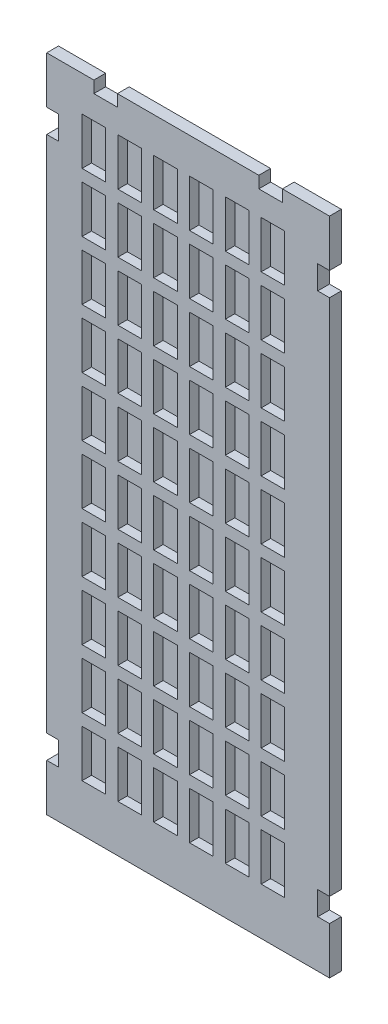
SolidWorks part; units mm, degrees
ref_plane "Front Plane" through (0, 0, 0) normal (0, 0, 1) x (1, 0, 0)
ref_plane "Top Plane" through (0, 0, 0) normal (0, 1, 0) x (1, 0, 0)
ref_plane "Right Plane" through (0, 0, 0) normal (1, 0, 0) x (0, 0, -1)
sketch "Sketch1" plane through (0, 0, 0) normal (0, 0, 1) x (1, 0, 0)
  line L0 (12.7, -177.8) -> (63.5, -177.8)
  line L1 (0, 0) -> (76.2, 0)
  line L2 (0, 0) -> (0, -177.8)
  line L3 (0, -177.8) -> (12.7, -177.8)
  line L4 (76.2, 0) -> (76.2, -177.8)
  line L5 (12.7, 0) -> (19.05, 0)
  line L6 (12.7, 0) -> (12.7, -3.175)
  line L7 (12.7, -3.175) -> (19.05, -3.175)
  line L8 (19.05, 0) -> (19.05, -3.175)
  line L9 (57.15, 0) -> (63.5, 0)
  line L10 (57.15, 0) -> (57.15, -3.175)
  line L11 (57.15, -3.175) -> (63.5, -3.175)
  line L12 (63.5, 0) -> (63.5, -3.175)
  line L13 (76.2, -12.7) -> (73.025, -12.7)
  line L14 (76.2, -12.7) -> (76.2, -19.05)
  line L15 (76.2, -19.05) -> (73.025, -19.05)
  line L16 (73.025, -12.7) -> (73.025, -19.05)
  line L17 (76.2, -158.75) -> (73.025, -158.75)
  line L18 (76.2, -158.75) -> (76.2, -165.1)
  line L19 (76.2, -165.1) -> (73.025, -165.1)
  line L20 (73.025, -158.75) -> (73.025, -165.1)
  line L25 (63.5, -177.8) -> (76.2, -177.8)
  line L29 (0, -165.1) -> (3.175, -165.1)
  line L30 (0, -165.1) -> (0, -158.75)
  line L31 (0, -158.75) -> (3.175, -158.75)
  line L32 (3.175, -165.1) -> (3.175, -158.75)
  line L33 (0, -19.05) -> (3.175, -19.05)
  line L34 (0, -19.05) -> (0, -12.7)
  line L35 (0, -12.7) -> (3.175, -12.7)
  line L36 (3.175, -19.05) -> (3.175, -12.7)
  dimension "D1" = 76.2
  dimension "D2" = 177.8
  dimension "D3" = 12.7
  dimension "D4" = 6.35
  dimension "D5" = 3.175
  dimension "D6" = 6.35
  dimension "D7" = 3.175
  dimension "D8" = 12.7
  dimension "D9" = 12.7
  dimension "D10" = 6.35
  dimension "D11" = 3.175
  dimension "D12" = 3.175
  dimension "D13" = 6.35
  dimension "D14" = 12.7
  dimension "D21" = 3.175
  dimension "D22" = 6.35
  dimension "D23" = 12.7
  dimension "D24" = 12.7
  dimension "D25" = 6.35
  dimension "D26" = 3.175
extrude "Boss-Extrude1" add sketch "Sketch1" along normal blind 3.175
sketch "Sketch2" plane through (0, 0, 3.175) normal (0, 0, 1) x (1, 0, 0)
  line L0 (12.7, -3.175) -> (19.05, -3.175) construction
  line L1 (9.525, -9.525) -> (15.875, -9.525)
  line L2 (9.525, -9.525) -> (9.525, -22.225)
  line L3 (9.525, -22.225) -> (15.875, -22.225)
  line L4 (15.875, -9.525) -> (15.875, -22.225)
  line L5 (9.525, -9.525) -> (15.875, -22.225) construction
  line L6 (9.525, -22.225) -> (15.875, -9.525) construction
  line L7 (3.175, -19.05) -> (3.175, -12.7) construction
  point P0 (12.7, -15.875)
  dimension "D1" = 6.35
  dimension "D2" = 6.35
  dimension "D3" = 12.7
  dimension "D4" = 6.35
extrude "Cut-Extrude1" cut sketch "Sketch2" against normal blind 2.54
pattern_linear "LPattern1" count 6 spacing 9.652 along (1, 0, 0) count 10 spacing 15.875 along (0, -1, 0) of "Cut-Extrude1"
